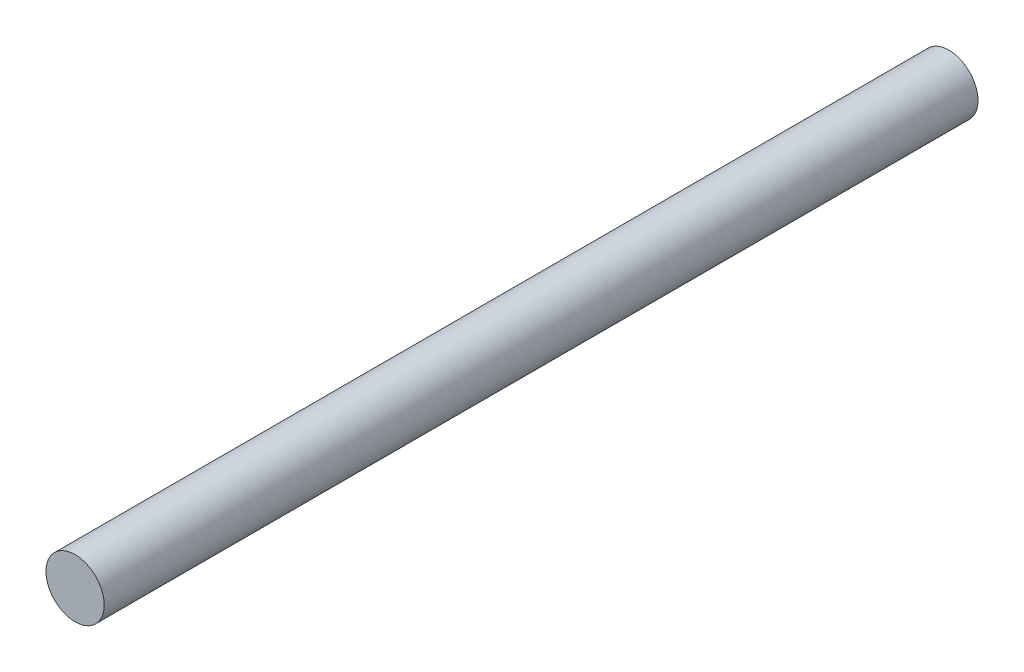
SolidWorks part; units mm, degrees
ref_plane "Front Plane" through (0, 0, 0) normal (0, 0, 1) x (1, 0, 0)
ref_plane "Top Plane" through (0, 0, 0) normal (0, 1, 0) x (1, 0, 0)
ref_plane "Right Plane" through (0, 0, 0) normal (1, 0, 0) x (0, 0, -1)
sketch "Sketch1" plane through (0, 0, 0) normal (0, 0, 1) x (1, 0, 0)
  circle A0 centre (0, 0) radius 5
  dimension "D1" = 10
extrude "Boss-Extrude1" add sketch "Sketch1" along normal mid plane 150
